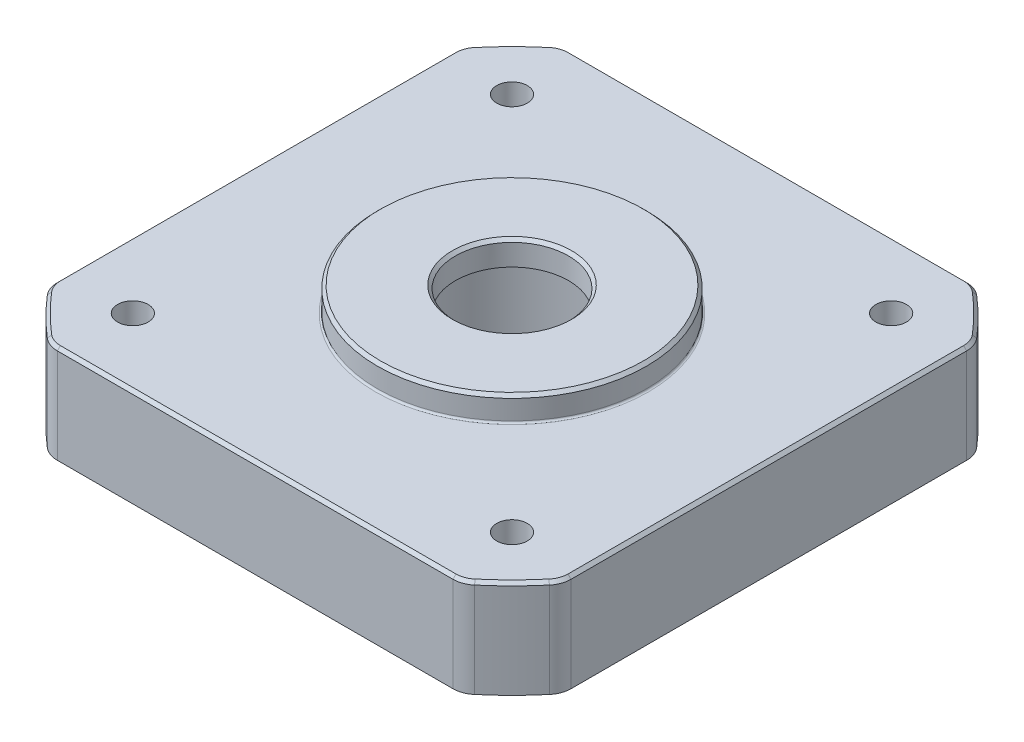
SolidWorks part; units mm, degrees
material "7075-T6, Plate (SS)"
ref_plane "Front" through (0, 0, 0) normal (0, 0, 1) x (1, 0, 0)
ref_plane "Top" through (0, 0, 0) normal (0, 1, 0) x (1, 0, 0)
ref_plane "Right" through (0, 0, 0) normal (1, 0, 0) x (0, 0, -1)
ref_plane "Plane1" through (0, 0, 0) normal (0, -1, 0) x (1, 0, 0)
sketch "Sketch1" plane through (0, 0, 0) normal (0, -1, 0) x (1, 0, 0)
  line L0 (16.171, 21) -> (-16.171, 21)
  line L1 (-21, 16.171) -> (-21, -16.171)
  line L2 (-16.171, -21) -> (16.171, -21)
  line L3 (21, -16.171) -> (21, 16.171)
  arc A0 (20.523, 17.4673) -> (17.4673, 20.523) centre (0, 0) ccw
  arc A1 (17.4673, 20.523) -> (16.171, 21) centre (16.171, 19) ccw
  arc A2 (-16.171, 21) -> (-17.4673, 20.523) centre (-16.171, 19) ccw
  arc A3 (-17.4673, 20.523) -> (-20.523, 17.4673) centre (0, 0) ccw
  arc A4 (-20.523, 17.4673) -> (-21, 16.171) centre (-19, 16.171) ccw
  arc A5 (-21, -16.171) -> (-20.523, -17.4673) centre (-19, -16.171) ccw
  arc A6 (-20.523, -17.4673) -> (-17.4673, -20.523) centre (0, 0) ccw
  arc A7 (-17.4673, -20.523) -> (-16.171, -21) centre (-16.171, -19) ccw
  arc A8 (16.171, -21) -> (17.4673, -20.523) centre (16.171, -19) ccw
  arc A9 (17.4673, -20.523) -> (20.523, -17.4673) centre (0, 0) ccw
  arc A10 (20.523, -17.4673) -> (21, -16.171) centre (19, -16.171) ccw
  arc A11 (21, 16.171) -> (20.523, 17.4673) centre (19, 16.171) ccw
extrude "Boss-Extrude1" add sketch "Sketch1" against normal blind 8
sketch "Sketch2" plane through (0, 0, 0) normal (0, -1, 0) x (1, 0, 0)
  line L0 (-19.5, 8.0772) -> (-19.5, -8.0772)
  line L1 (-19.5, -8.0772) -> (-8.0772, -19.5)
  line L2 (-8.0772, -19.5) -> (8.0772, -19.5)
  line L3 (8.0772, -19.5) -> (19.5, -8.0772)
  line L4 (19.5, -8.0772) -> (19.5, 8.0772)
  line L5 (19.5, 8.0772) -> (8.0772, 19.5)
  line L6 (8.0772, 19.5) -> (-8.0772, 19.5)
  line L7 (-8.0772, 19.5) -> (-19.5, 8.0772)
extrude "Cut-Extrude1" cut sketch "Sketch2" against normal blind 7
sketch "Sketch3" plane through (0, 8, 0) normal (0, 1, 0) x (-1, 0, 0)
  circle A0 centre (0, 0) radius 11
extrude "Boss-Extrude2" add sketch "Sketch3" along normal blind 2
sketch "Sketch4" plane through (0, 7, 0) normal (0, -1, 0) x (1, 0, 0)
  circle A0 centre (0, 0) radius 12.925
extrude "Boss-Extrude3" add sketch "Sketch4" along normal blind 8
ref_plane "Plane2" through (0, 7, 0) normal (0, 1, 0) x (1, 0, 0)
sketch "Sketch5" plane through (0, 7, 0) normal (0, 1, 0) x (1, 0, 0)
  circle A0 centre (0, 0) radius 8.025
extrude "Cut-Extrude2" cut sketch "Sketch5" against normal through all
ref_plane "Plane3" through (0, 8, 0) normal (0, 1, 0) x (1, 0, 0)
sketch "Sketch6" plane through (0, 8, 0) normal (0, 1, 0) x (1, 0, 0)
  circle A0 centre (0, 0) radius 6.125
extrude "Cut-Extrude3" cut sketch "Sketch6" against normal through all
hole_wizard "M8 Clearance Hole1" positions "Sketch8" profile "Sketch7" hole size "M8" standard "ANSI Metric"
sketch "Sketch8" plane through (0, 10, 0) normal (0, 1, 0) x (1, 0, 0)
  point P0 (0, 0)
sketch "Sketch7" plane through (0, 10, 0) normal (1, 0, 0) x (0, 0, 1)
  line L0 (0, 0) -> (0, 11)
  line L1 (0, 11) -> (4.625, 11)
  line L2 (4.625, 11) -> (4.625, 0)
  line L5 (4.625, 0) -> (0, 0)
  line L11 (0, -6.35) -> (0, 107.95) construction
  dimension "Thru Hole Dia." = 9.25
  dimension "Thru Hole Depth" = 11
hole_wizard "Ø2.5 (2.5) Diameter Hole1" positions "Sketch10" profile "Sketch9" hole size "Ø2.5" standard "ANSI Metric"
sketch "Sketch10" plane through (0, 0, 0) normal (0, -1, 0) x (-1, 0, 0)
  point P0 (15.5, 15.5)
  point P1 (-15.5, -15.5)
  point P2 (-15.5, 15.5)
  point P3 (15.5, -15.5)
sketch "Sketch9" plane through (-15.5, 0, -15.5) normal (1, 0, 0) x (0, 0, -1)
  line L0 (0, 0) -> (0, 10)
  line L1 (0, 10) -> (1.25, 10)
  line L2 (1.25, 10) -> (1.25, 0)
  line L5 (1.25, 0) -> (0, 0)
  line L11 (0, -6.35) -> (0, 107.95) construction
  dimension "Thru Hole Dia." = 2.5
  dimension "Thru Hole Depth" = 10
fillet "Fillet1" radius 0.15 2 edges at (0, 8, -11) (0, 7, -12.925)
fillet "Fillet2" radius 0.5 8 edges at (-19.5, 3.5, -8.0772) (8.0772, 3.5, -19.5) (19.5, 3.5, -8.0772) (19.5, 3.5, 8.0772) (8.0772, 3.5, 19.5) (-8.0772, 3.5, 19.5) (-19.5, 3.5, 8.0772) (-8.0772, 3.5, -19.5)
chamfer "Chamfer1" distance 0.5 angle 63.435 1 edges at (0, -1, -8.025)
chamfer "Chamfer2" distance 0.25 angle 45 16 edges at (0, 8, 21) (16.8617, 8, 20.877) (-16.8617, 8, 20.877) (19.0565, 8, 19.0565) (-19.0565, 8, 19.0565) (20.877, 8, 16.8617) (-20.877, 8, 16.8617) (21, 8, 0) (-21, 8, 0) (20.877, 8, -16.8617) (-20.877, 8, -16.8617) (19.0565, 8, -19.0565) (-19.0565, 8, -19.0565) (16.8617, 8, -20.877) (-16.8617, 8, -20.877) (0, 8, -21)
chamfer "Chamfer3" distance 0.25 angle 45 4 edges at (0, 7, -6.125) (0, -1, -12.925) (0, 10, 11) (0, 10, 4.625)
